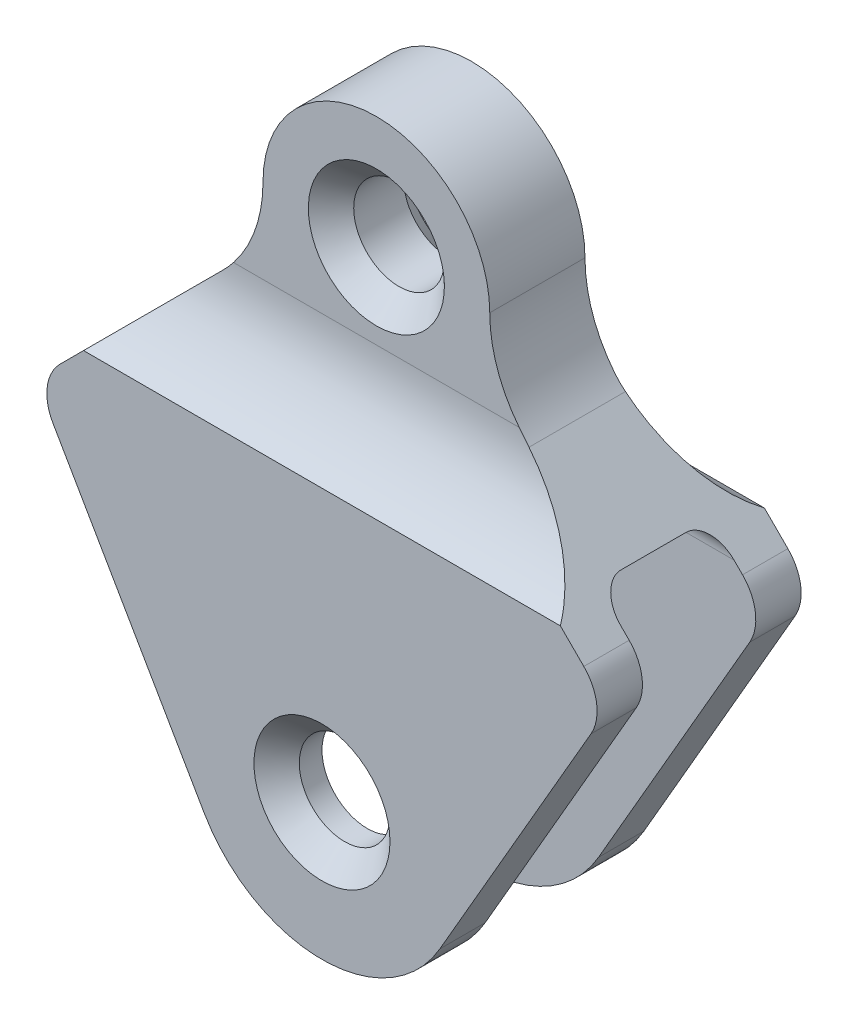
SolidWorks part; units mm, degrees
ref_plane "Front Plane" through (0, 0, 0) normal (0, 0, 1) x (1, 0, 0)
ref_plane "Top Plane" through (0, 0, 0) normal (0, 1, 0) x (1, 0, 0)
ref_plane "Right Plane" through (0, 0, 0) normal (1, 0, 0) x (0, 0, -1)
sketch "Sketch2" plane through (0, 0, 0) normal (0, 0, 1) x (1, 0, 0)
  line L0 (0, -30) -> (0, 111.7726) construction
  line L1 (25.9808, -15) -> (59.3297, 42.762)
  line L2 (57.7405, 54.8331) -> (33.7868, 78.7868)
  line L3 (-25.9808, -15) -> (-59.3297, 42.762)
  line L4 (-57.7405, 54.8331) -> (-33.7868, 78.7868)
  circle A0 centre (0, 0) radius 10
  circle A1 centre (0, 100) radius 10
  arc A2 (-25.9808, -15) -> (25.9808, -15) centre (0, 0) ccw
  arc A3 (59.3297, 42.762) -> (57.7405, 54.8331) centre (50.6694, 47.762) ccw
  arc A4 (33.7868, 78.7868) -> (25, 100) centre (55, 100) cw
  arc A5 (25, 100) -> (-3.7445, 124.718) centre (0, 100) ccw
  arc A6 (-59.3297, 42.762) -> (-57.7405, 54.8331) centre (-50.6694, 47.762) cw
  arc A7 (-25, 100) -> (3.7445, 124.718) centre (0, 100) cw
  arc A8 (-33.7868, 78.7868) -> (-25, 100) centre (-55, 100) ccw
  point P17 (0, 0)
  point P18 (0, 0)
  dimension "D1" = 20
  dimension "D3" = 20
  dimension "D4" = 25
  dimension "D5" = 30
  dimension "D7" = 10
  dimension "D2" = 100
  dimension "D6" = 45
  dimension "D8" = 30
extrude "Boss-Extrude1" add sketch "Sketch2" along normal blind 45
sketch "Sketch3" plane through (0, 0, 0) normal (1, 0, 0) x (0, 0, -1)
  line L0 (-22.5, -42.2341) -> (-22.5, -30) construction
  line L1 (-45, 125) -> (-33, 125)
  line L2 (0, 125) -> (-45, 125) construction
  line L3 (-33, 125) -> (-33, 81.3542)
  line L4 (-45, 54.8331) -> (-45, 78.7868) construction
  line L5 (-45, 60) -> (-45, 125)
  line L6 (-10, -30) -> (-35, -30)
  line L7 (-45, -30) -> (0, -30) construction
  line L8 (-35, -30) -> (-35, 56.7047)
  line L10 (-29.7047, 62) -> (-15.2953, 62)
  line L11 (-22.5, 61.6825) -> (-22.5, 159.4015) construction
  line L12 (-22.5, 62) -> (-22.5, -30)
  line L13 (-10, -30) -> (-10, 56.7047)
  line L14 (0, 60) -> (0, 125)
  line L15 (-12, 125) -> (-12, 81.3542)
  line L16 (0, 125) -> (-12, 125)
  arc A0 (-33, 81.3542) -> (-45, 60) centre (-58, 81.3542) cw
  arc A2 (-35, 56.7047) -> (-29.7047, 62) centre (-29.7047, 56.7047) cw
  arc A3 (-10, 56.7047) -> (-15.2953, 62) centre (-15.2953, 56.7047) ccw
  arc A4 (-12, 81.3542) -> (0, 60) centre (13, 81.3542) ccw
  dimension "D3" = 25
  dimension "D5" = 92
  dimension "D6" = 5.2953
  dimension "D1" = 65
  dimension "D2" = 12
  dimension "D4" = 12.5
extrude "Cut-Extrude2" cut sketch "Sketch3" against normal through all and the other way through all contours L15 A4 L14 L16 | A2 L8 L6 L12 L10 | L13 A3 L10 L12 L6 | L3 A0 L5 L1
chamfer "Chamfer1" distance 5 angle 45 4 edges at (10, 0, 45) (10, 0, 0) (0, 90, 12) (0, 90, 33)
